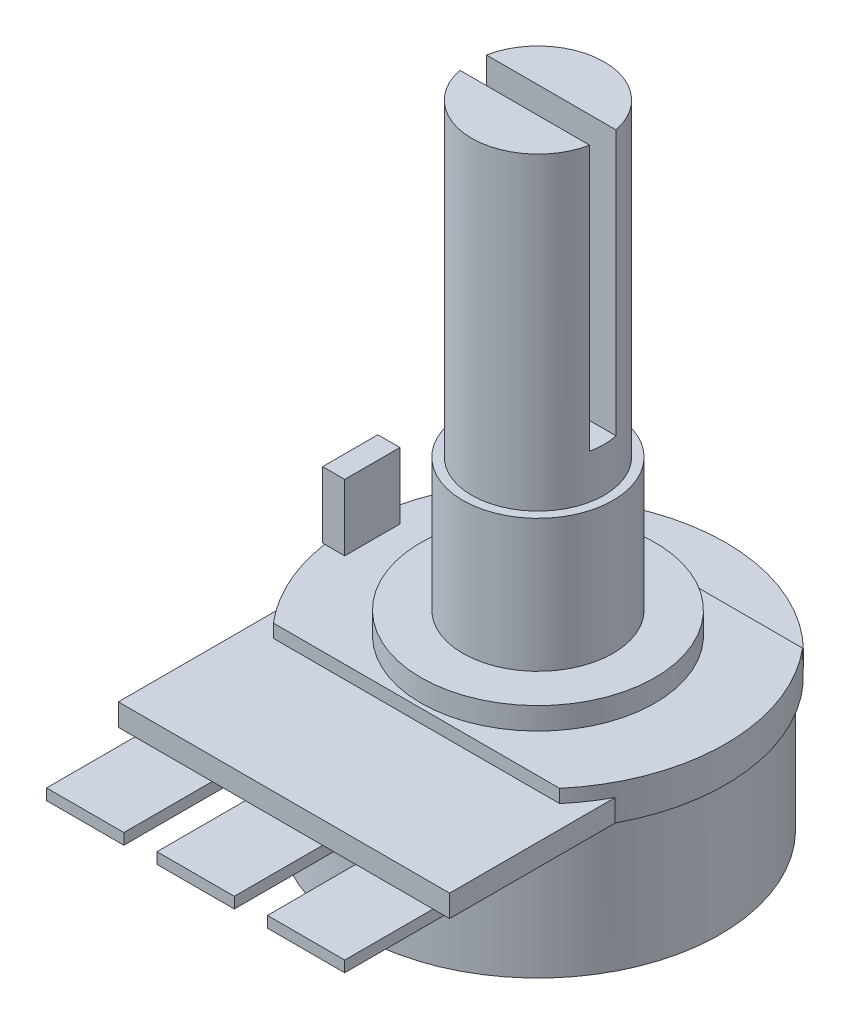
SolidWorks part; units mm, degrees
ref_plane "Front Plane" through (0, 0, 0) normal (0, 0, 1) x (1, 0, 0)
ref_plane "Top Plane" through (0, 0, 0) normal (0, 1, 0) x (1, 0, 0)
ref_plane "Right Plane" through (0, 0, 0) normal (1, 0, 0) x (0, 0, -1)
sketch "Sketch1" plane through (0, 0, 0) normal (0, 1, 0) x (1, 0, 0)
  circle A0 centre (0, 0) radius 5.3
  dimension "D1" = 10.6
extrude "Boss-Extrude1" add sketch "Sketch1" against normal blind 1
sketch "Sketch2" plane through (0, 0, 0) normal (0, 1, 0) x (1, 0, 0)
  circle A0 centre (0, 0) radius 3.4
  dimension "D1" = 6.8
extrude "Boss-Extrude2" add sketch "Sketch2" along normal blind 6
sketch "Sketch3" plane through (0, 6, 0) normal (0, 1, 0) x (1, 0, 0)
  circle A0 centre (0, 0) radius 3
  dimension "D1" = 6
extrude "Boss-Extrude3" add sketch "Sketch3" along normal blind 14
sketch "Sketch4" plane through (0, 20, 0) normal (0, 1, 0) x (1, 0, 0)
  line L1 (-4, -0.6) -> (4, -0.6)
  line L2 (-4, -0.6) -> (-4, 0.6)
  line L3 (-4, 0.6) -> (4, 0.6)
  line L4 (4, -0.6) -> (4, 0.6)
  line L5 (-4, -0.6) -> (4, 0.6) construction
  line L6 (-4, 0.6) -> (4, -0.6) construction
  point P0 (0, 0)
  dimension "D1" = 8
  dimension "D2" = 1.2
extrude "Cut-Extrude1" cut sketch "Sketch4" against normal blind 12
sketch "Sketch5" plane through (0, -1, 0) normal (0, -1, 0) x (1, 0, 0)
  line L0 (-6.4807, 5.5) -> (6.4807, 5.5)
  line L3 (-6.4807, -5.5) -> (6.4807, -5.5)
  arc A0 (-6.4807, 5.5) -> (-6.4807, -5.5) centre (0, 0) ccw
  arc A1 (6.4807, -5.5) -> (6.4807, 5.5) centre (0, 0) ccw
  point P3 (0, 0)
  point P6 (0, 0)
  point P9 (0, 0)
  dimension "D1" = 17
  dimension "D2" = 11
  dimension "D3" = 11
extrude "Boss-Extrude4" add sketch "Sketch5" along normal blind 0.6
sketch "Sketch6" plane through (0, -1.6, 0) normal (0, -1, 0) x (1, 0, 0)
  line L2 (7.5, 4) -> (7.5, 11.5)
  line L3 (7.5, 11.5) -> (-7.5, 11.5)
  line L4 (-7.5, 4) -> (-7.5, 11.5)
  arc A0 (-7.5, 4) -> (7.5, 4) centre (0, 0) ccw
  point P3 (0, 11.5)
  point P8 (0, 0)
  point P9 (0, 0)
  point P10 (0, 0)
  dimension "D1" = 17
  dimension "D2" = 11.5
  dimension "D3" = 15
extrude "Boss-Extrude5" add sketch "Sketch6" along normal blind 1
sketch "Sketch7" plane through (0, -2.6, 0) normal (0, -1, 0) x (1, 0, 0)
  circle A0 centre (0, 0) radius 8.25
  dimension "D1" = 16.5
extrude "Boss-Extrude6" add sketch "Sketch7" along normal blind 6
sketch "Sketch8" plane through (0, -2.6, 0) normal (0, -1, 0) x (1, 0, 0)
  line L0 (7.5, 11.5) -> (-7.5, 11.5) construction
  line L1 (-6.75, 7.5) -> (-3.25, 7.5)
  line L2 (-6.75, 7.5) -> (-6.75, 15.5)
  line L3 (-6.75, 15.5) -> (-3.25, 15.5)
  line L4 (-3.25, 7.5) -> (-3.25, 15.5)
  line L5 (-1.75, 7.5) -> (-1.75, 15.5)
  line L6 (-1.75, 7.5) -> (1.75, 7.5)
  line L7 (1.75, 7.5) -> (1.75, 15.5)
  line L8 (-1.75, 15.5) -> (1.75, 15.5)
  line L9 (3.25, 7.5) -> (3.25, 15.5)
  line L10 (3.25, 7.5) -> (6.75, 7.5)
  line L11 (6.75, 7.5) -> (6.75, 15.5)
  line L12 (3.25, 15.5) -> (6.75, 15.5)
  point P7 (0, 15.5)
  dimension "D1" = 4
  dimension "D2" = 4
  dimension "D3" = 3.5
  dimension "D5" = 1.5
  dimension "D4" = 3
extrude "Boss-Extrude7" add sketch "Sketch8" along normal blind 0.5
sketch "Sketch9" plane through (0, -1, 0) normal (0, 1, 0) x (1, 0, 0)
  line L1 (-8.5, 1.25) -> (-7.5, 1.25)
  line L2 (-8.5, 1.25) -> (-8.5, -1.25)
  line L3 (-8.5, -1.25) -> (-7.5, -1.25)
  line L4 (-7.5, 1.25) -> (-7.5, -1.25)
  line L5 (-8.5, 1.25) -> (-7.5, -1.25) construction
  line L6 (-8.5, -1.25) -> (-7.5, 1.25) construction
  arc A0 (-6.4807, 5.5) -> (-6.4807, -5.5) centre (0, 0) ccw construction
  point P0 (-8, 0)
  point P5 (0, 0)
  dimension "D1" = 1
  dimension "D2" = 2.5
extrude "Boss-Extrude8" add sketch "Sketch9" along normal blind 3
